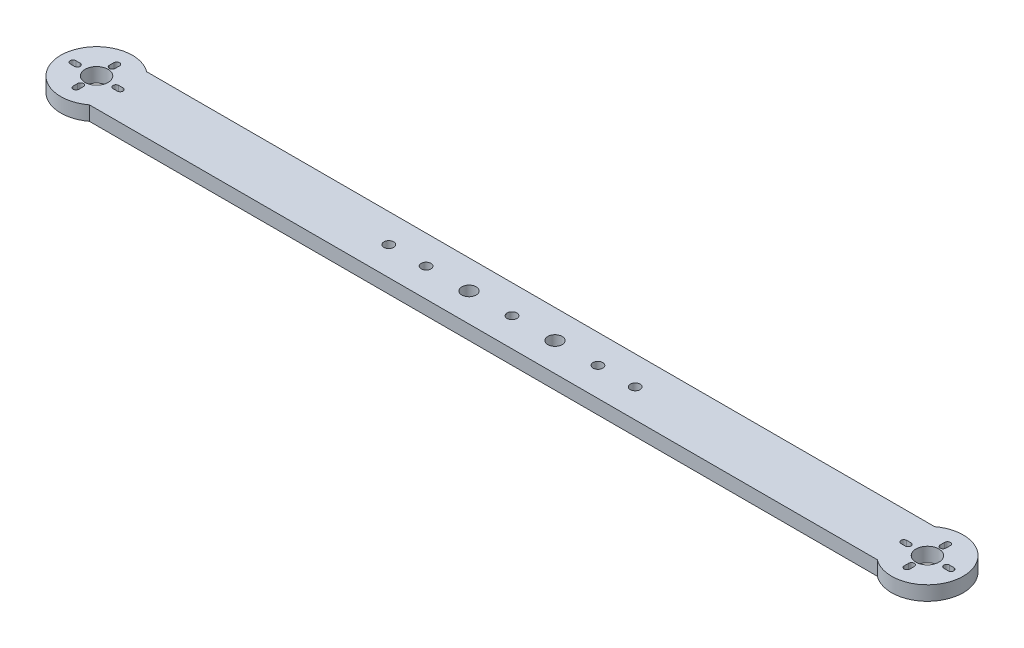
SolidWorks part; units mm, degrees
ref_plane "Front Plane" through (0, 0, 0) normal (0, 0, 1) x (1, 0, 0)
ref_plane "Top Plane" through (0, 0, 0) normal (0, 1, 0) x (1, 0, 0)
ref_plane "Right Plane" through (0, 0, 0) normal (1, 0, 0) x (0, 0, -1)
sketch "Sketch1" plane through (0, 0, 0) normal (0, 1, 0) x (1, 0, 0)
  line L0 (0, 12.7) -> (0, -12.7) construction
  line L1 (-174.625, 12.7) -> (174.625, 12.7)
  line L3 (-174.625, -12.7) -> (174.625, -12.7)
  arc A0 (-174.625, 12.7) -> (-174.625, -12.7) centre (-184.15, 0) ccw
  arc A1 (174.625, -12.7) -> (174.625, 12.7) centre (184.15, 0) ccw
  point P8 (0, 12.7)
  point P12 (0, 0)
  dimension "D3" = 31.75
  dimension "D4" = 31.75
extrude "Boss-Extrude1" add sketch "Sketch1" along normal blind 6.35
sketch "Sketch2" plane through (0, 6.35, 0) normal (0, 1, 0) x (1, 0, 0)
  line L0 (173.6914, 0) -> (175.6086, 0) construction
  line L1 (173.6914, 1.25) -> (175.6086, 1.25)
  line L2 (173.6914, -1.25) -> (175.6086, -1.25)
  line L3 (184.15, 0) -> (184.15, 3.2374) construction
  line L4 (194.6086, 0) -> (192.6914, 0) construction
  line L5 (194.6086, 1.25) -> (192.6914, 1.25)
  line L6 (194.6086, -1.25) -> (192.6914, -1.25)
  line L7 (184.15, 8.9209) -> (184.15, 6.921) construction
  line L8 (185.4, 8.9209) -> (185.4, 6.921)
  line L9 (182.9, 8.9209) -> (182.9, 6.921)
  line L10 (184.1914, -9.079) -> (184.1914, -7.079) construction
  line L11 (185.4414, -9.079) -> (185.4414, -7.079)
  line L12 (182.9414, -9.079) -> (182.9414, -7.079)
  line L13 (0, 0) -> (184.15, 0) construction
  line L14 (0, 0) -> (0, 12.7) construction
  line L15 (174.625, 12.7) -> (-174.625, 12.7) construction
  line L16 (-184.15, 0) -> (-184.15, 3.2374) construction
  line L17 (-184.1914, -9.079) -> (-184.1914, -7.079) construction
  line L18 (-185.4414, -9.079) -> (-185.4414, -7.079)
  line L19 (-182.9414, -9.079) -> (-182.9414, -7.079)
  line L20 (-184.15, 8.9209) -> (-184.15, 6.921) construction
  line L21 (-185.4, 8.9209) -> (-185.4, 6.921)
  line L22 (-182.9, 8.9209) -> (-182.9, 6.921)
  line L23 (-194.6086, 0) -> (-192.6914, 0) construction
  line L24 (-194.6086, 1.25) -> (-192.6914, 1.25)
  line L25 (-194.6086, -1.25) -> (-192.6914, -1.25)
  line L26 (-173.6914, 0) -> (-175.6086, 0) construction
  line L27 (-173.6914, 1.25) -> (-175.6086, 1.25)
  line L28 (-173.6914, -1.25) -> (-175.6086, -1.25)
  circle A0 centre (184.15, 0) radius 5.08
  arc A1 (173.6914, 1.25) -> (173.6914, -1.25) centre (173.6914, 0) ccw
  arc A2 (175.6086, -1.25) -> (175.6086, 1.25) centre (175.6086, 0) ccw
  arc A3 (194.6086, 1.25) -> (194.6086, -1.25) centre (194.6086, 0) cw
  arc A4 (192.6914, -1.25) -> (192.6914, 1.25) centre (192.6914, 0) cw
  arc A5 (185.4, 8.9209) -> (182.9, 8.9209) centre (184.15, 8.9209) ccw
  arc A6 (182.9, 6.921) -> (185.4, 6.921) centre (184.15, 6.921) ccw
  arc A7 (185.4414, -9.079) -> (182.9414, -9.079) centre (184.1914, -9.079) cw
  arc A8 (182.9414, -7.079) -> (185.4414, -7.079) centre (184.1914, -7.079) cw
  circle A9 centre (-184.15, 0) radius 5.08
  arc A10 (-185.4414, -9.079) -> (-182.9414, -9.079) centre (-184.1914, -9.079) ccw
  arc A11 (-182.9414, -7.079) -> (-185.4414, -7.079) centre (-184.1914, -7.079) ccw
  arc A12 (-185.4, 8.9209) -> (-182.9, 8.9209) centre (-184.15, 8.9209) cw
  arc A13 (-182.9, 6.921) -> (-185.4, 6.921) centre (-184.15, 6.921) cw
  arc A14 (-194.6086, 1.25) -> (-194.6086, -1.25) centre (-194.6086, 0) ccw
  arc A15 (-192.6914, -1.25) -> (-192.6914, 1.25) centre (-192.6914, 0) ccw
  arc A16 (-173.6914, 1.25) -> (-173.6914, -1.25) centre (-173.6914, 0) cw
  arc A17 (-175.6086, -1.25) -> (-175.6086, 1.25) centre (-175.6086, 0) cw
  point P4 (174.65, 0)
  point P12 (193.65, 0)
  point P19 (184.15, 7.921)
  point P26 (184.1914, -8.079)
  point P41 (-184.1914, -8.079)
  point P48 (-184.15, 7.921)
  point P55 (-193.65, 0)
  point P62 (-174.65, 0)
  dimension "D4" = 10.16
  dimension "D1" = 16
  dimension "D2" = 19
  dimension "D3" = 184.15
  dimension "D5" = 1.9999
extrude "Cut-Extrude1" cut sketch "Sketch2" against normal through all
sketch "Sketch3" plane through (0, 6.35, 0) normal (0, 1, 0) x (1, 0, 0)
  circle A0 centre (0, 0) radius 2.159
  circle A1 centre (38.1, 0) radius 2.159
  circle A2 centre (-38.1, 0) radius 2.159
  dimension "D1" = 38.1
  dimension "D3" = 4.318
  dimension "D4" = 4.318
  dimension "D5" = 4.318
  dimension "D2" = 38.1
extrude "Cut-Extrude2" cut sketch "Sketch3" against normal through all
sketch "Sketch4" plane through (0, 6.35, 0) normal (0, 1, 0) x (1, 0, 0)
  circle A0 centre (-19.05, 0) radius 3.175
  circle A1 centre (19.05, 0) radius 3.175
  dimension "D1" = 19.05
  dimension "D2" = 19.05
extrude "Cut-Extrude3" cut sketch "Sketch4" against normal through all
sketch "Sketch6" plane through (0, 0, 0) normal (0, -1, 0) x (-1, 0, 0)
  circle A0 centre (54.61, 0) radius 2.159
  circle A1 centre (-19.05, 0) radius 3.175 construction
  circle A2 centre (-54.61, 0) radius 2.159
  circle A4 centre (19.05, 0) radius 3.175 construction
  dimension "D1" = 73.66
  dimension "D2" = 4.318
  dimension "D3" = 73.66
extrude "Cut-Extrude5" cut sketch "Sketch6" against normal through all
